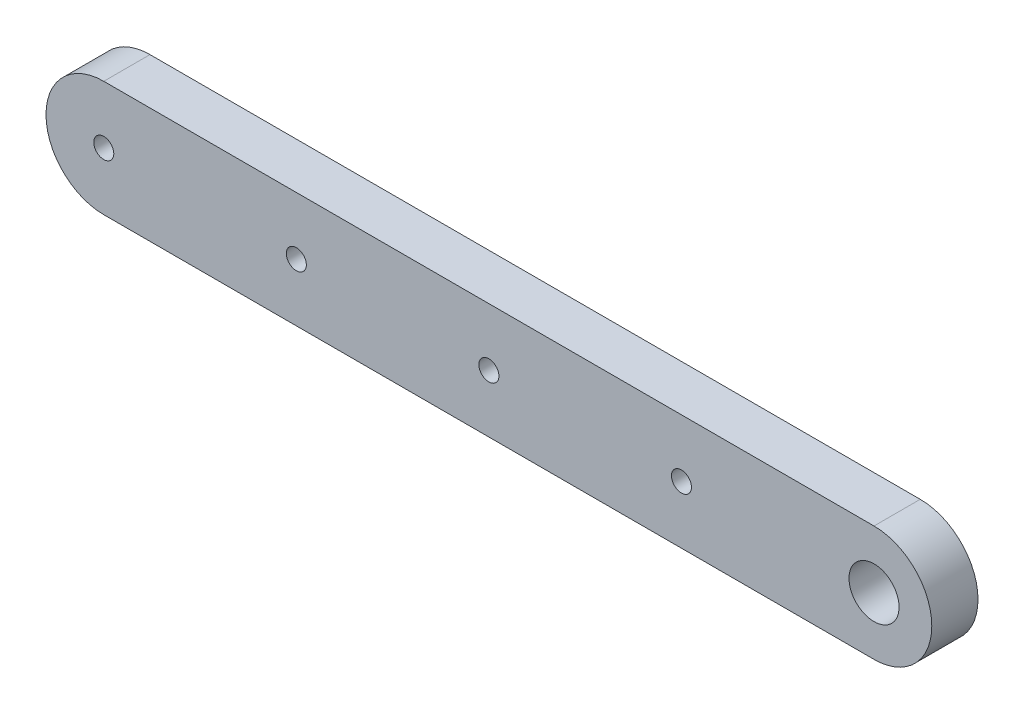
SolidWorks part; units mm, degrees
material "Pine"
ref_plane "Front Plane" through (0, 0, 0) normal (0, 0, 1) x (1, 0, 0)
ref_plane "Top Plane" through (0, 0, 0) normal (0, 1, 0) x (1, 0, 0)
ref_plane "Right Plane" through (0, 0, 0) normal (1, 0, 0) x (0, 0, -1)
sketch "Sketch1" plane through (0, 0, 0) normal (0, 0, 1) x (1, 0, 0)
  line L0 (0, 7.5) -> (100, 7.5)
  line L1 (100, -7.5) -> (0, -7.5)
  circle A0 centre (0, 0) radius 7.5
  circle A1 centre (100, 0) radius 7.5
  dimension "D1" = 100
  dimension "D2" = 15
extrude "Boss-Extrude1" add sketch "Sketch1" along normal blind 6 contours A1 L0 A0 L1 | A1 | A0
ref_plane "Plane1" through (0, 0, 3) normal (0, 0, 1) x (1, 0, 0)
sketch "Sketch2" plane through (0, 0, 6) normal (0, 0, 1) x (1, 0, 0)
  circle A0 centre (0, 0) radius 1.3
  circle A1 centre (100, 0) radius 1.3
  dimension "D1" = 2.6
extrude "Cut-Extrude1" cut sketch "Sketch2" against normal through all
pattern_linear "LPattern1" count 4 spacing 25 along (1, 0, 0) of "Cut-Extrude1"
sketch "Sketch3" plane through (0, 0, 6) normal (0, 0, 1) x (1, 0, 0)
  circle A0 centre (100, 0) radius 3.25
  dimension "D1" = 6.5
extrude "Cut-Extrude2" cut sketch "Sketch3" against normal through all
